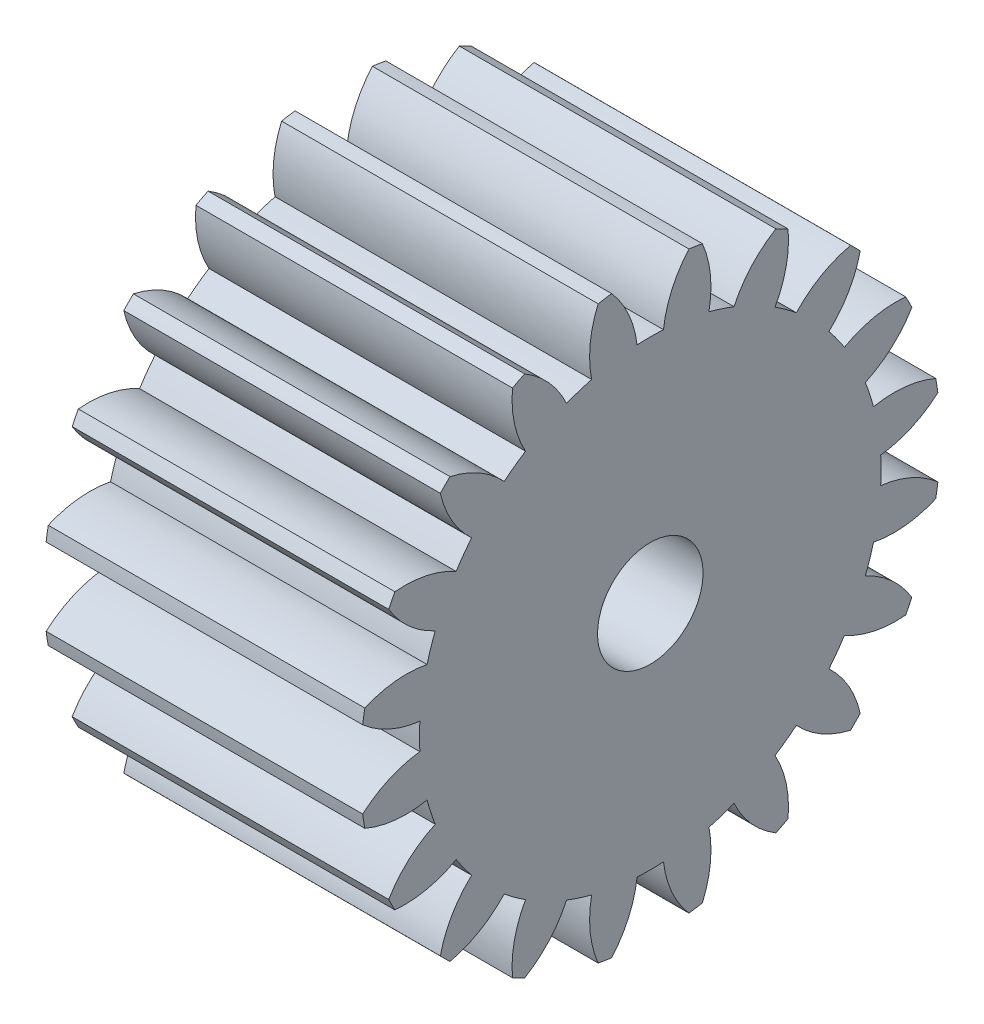
SolidWorks part; units mm, degrees
ref_plane "Plane1" through (0, 0, 0) normal (0, 0, 1) x (1, 0, 0)
ref_plane "Plane2" through (0, 0, 0) normal (0, 1, 0) x (1, 0, 0)
ref_plane "Plane3" through (0, 0, 0) normal (1, 0, 0) x (0, 0, -1)
other "Configuration Table"
sketch "HoldingSke" plane through (0, 0, 0) normal (0, 1, 0) x (1, 0, 0)
  line L0 (0, 0) -> (0.9397, -0.342)
  line L1 (-15, 0) -> (100, 0) construction
  line L2 (0, 0) -> (-2.1039, 2.3779)
  line L3 (0, 0) -> (-11.863, 4.5341)
  line L4 (0, 0) -> (8.1152, 2.9537)
  line L5 (0, 0) -> (-46.8476, -17.4728)
  line L6 (0, 0) -> (-9.9476, -6.7116)
  line L7 (-2.1039, 2.3779) -> (8.6586, 51.2059)
  line L8 (-76.2, 54.61) -> (-75.5, 54.61)
  line L9 (-71.009, 38.7566) -> (-53.1078, 45.2721)
  line L10 (-76.2, 71.12) -> (104.1128, 71.12)
  line L11 (0, 0) -> (-12, 0)
  line L12 (-76.2, 101.6) -> (-76.162, 101.6)
  line L13 (24.9733, 27.94) -> (52.9518, 28.4284)
  line L14 (24.9733, 27.94) -> (24.9743, 27.94)
  line L15 (24.9733, 27.94) -> (100.4006, 29.5858)
  line L16 (-63.627, -1) -> (-12.827, -1)
  circle A0 centre (0, 0) radius 2
  circle A1 centre (0, 0) radius 8.749
  circle A2 centre (0, 0) radius 37.5
  circle A3 centre (0, 0) radius 2
  dimension "MHD" = 17.498
  dimension "Hub_dia" = 75
  dimension "Bore" = 4
  dimension "MBD" = 4
  dimension "Num_teeth" = 20
  dimension "Pitch" = 1
  dimension "Overall_len" = 50
  dimension "Show_teeth" = 20
  dimension "Thickness" = 12
  dimension "OAL" = 50.0001
  dimension "T_dim" = 0.7
  dimension "Ap" = 20
  dimension "H" = 19.05
  dimension "Pitch_radius" = 180.3128
  dimension "Width" = 12
  dimension "Backlash" = 0.038
  dimension "Addendum_fac" = 1
  dimension "Dedendum_fac" = 1.25
  dimension "Clearance_fac" = 0.25
  dimension "Dedendum_add" = 0.001
  dimension "Module" = 1
sketch "BasProSke" plane through (0, 0, 0) normal (0, 1, 0) x (1, 0, 0)
  line L0 (-10, 0) -> (60, 0) construction
  line L1 (0, 0) -> (0, 11)
  line L2 (0, 0) -> (12, 0)
  line L3 (12, 0) -> (12, 11)
  line L4 (12, 11) -> (0, 11)
  dimension "Thickness" = 12
  dimension "Diameter" = 22
revolve "Base-Revolve" add sketch "BasProSke" angle 360 about L0
sketch "TooCutSke" plane through (0, 0, 0) normal (1, 0, 0) x (0, 0, -1)
  line L1 (0, 0) -> (0, 107) construction
  line L2 (0, 0) -> (-0.8511, 9.9637) construction
  line L3 (0, 0) -> (-3.1206, 19.7028) construction
  line L4 (-0.8511, 9.9637) -> (-1.5603, 9.8514) construction
  arc A0 (0.4999, 8.7347) -> (-0.4999, 8.7347) centre (0, 0) ccw
  arc A1 (1.4852, 10.9249) -> (-1.4852, 10.9249) centre (0, 0) ccw
  circle A2 centre (0, 0) radius 10 construction
  circle A3 centre (0, 0) radius 9.3969 construction
  arc A4 (-0.4999, 8.7347) -> (-1.4852, 10.9249) centre (-4.4722, 8.2645) ccw
  arc A5 (1.4852, 10.9249) -> (0.4999, 8.7347) centre (4.4722, 8.2645) ccw
  dimension "Root_dia" = 17.498
  dimension "Overcut_dia" = 22.0508
  dimension "Pitch_dia" = 20
  dimension "Base_dia" = 18.7939
  dimension "Flank_rad" = 4
  dimension "Half_ang" = 9
  dimension "Half_CT" = 0.7181
extrude "ToothCut" cut sketch "TooCutSke" along normal through all
fillet "Breaks" [suppressed] radius 0.02
fillet "RootFillets" [suppressed] radius 0.251
pattern_circular "TeethCuts" count 20 every 18 about axis through (-10, 0, 0) along (1, 0, 0) of "ToothCut", "RootFillets", "Breaks"
sketch "HubNeaOneSke" plane through (0, 0, 0) normal (-1, 0, 0) x (0, 0, 1)
  circle A0 centre (0, 0) radius 8.749
  dimension "Diameter" = 17.498
extrude "HubNearOne" [suppressed] add sketch "HubNeaOneSke" along normal blind 38.0001
sketch "HubNeaBotSke" plane through (0, 0, 0) normal (-1, 0, 0) x (0, 0, 1)
  circle A0 centre (0, 0) radius 8.749
  dimension "Diameter" = 17.498
extrude "HubNearBoth" [suppressed] add sketch "HubNeaBotSke" along normal blind 19
ref_plane "FarPln" through (12, 0, 0) normal (1, 0, 0) x (0, 0, -1)
sketch "HubFarSke" plane through (12, 0, 0) normal (1, 0, 0) x (0, 0, -1)
  circle A0 centre (0, 0) radius 8.749
  dimension "Diameter" = 17.498
extrude "HubFar" [suppressed] add sketch "HubFarSke" along normal blind 19
sketch "BorSke" plane through (0, 0, 0) normal (1, 0, 0) x (0, 0, -1)
  circle A0 centre (0, 0) radius 2
  dimension "Diameter" = 4
extrude "Bore" cut sketch "BorSke" along normal mid plane 100.0001
sketch "KeySke" plane through (0, 0, 0) normal (1, 0, 0) x (0, 0, -1)
  line L0 (-0.8, 0) -> (-0.8, 2.7)
  line L1 (-0.8, 2.7) -> (0.8, 2.7)
  line L2 (0.8, 2.7) -> (0.8, 0)
  line L3 (0, 0) -> (0, 34) construction
  line L4 (-0.8, 0) -> (0.8, 0)
  dimension "Offset" = 2.7
  dimension "Width" = 1.6
extrude "Keyway" [suppressed] cut sketch "KeySke" along normal mid plane 100.0001
pattern_circular "Keyway2" [suppressed] count 2 every 90 about axis through (-10, 0, 0) along (1, 0, 0)
equation "' \"Module@HoldingSke\" = 6.35"
equation "' \"Num_teeth@HoldingSke\" = 12"
equation "' \"Ap@HoldingSke\" =  20"
equation "' \"Ap@HoldingSke\" = 20"
equation "' \"Width@HoldingSke\" = 0.5 * 25.4"
equation "' \"Hub_dia@HoldingSke\"= 1 * 25.4"
equation "' \"Hub_dia@HoldingSke\" = 1 * 25.4"
equation "' \"Overall_len@HoldingSke\" = 1.0 * 25.4"
equation "' \"Bore@HoldingSke\" = 0.75 * 25.4"
equation "' \"T_dim@HoldingSke\" = 0.1 * 25.4"
equation "' \"Width@KeySke\" = 0.25 * 25.4"
equation "' \"Show_teeth@HoldingSke\" = 13"
equation "' \"Backlash@HoldingSke\" = 0.009 * 25.4"
equation "' \"Addendum_fac@HoldingSke\" = 1.0"
equation "' \"Dedendum_fac@HoldingSke\" = 1.25"
equation "' \"Dedendum_add@HoldingSke\" = 0.00005 * 25.4"
equation "' \"Clearance_fac@HoldingSke\" = 0.25"
equation "\"Pitch@HoldingSke\" = 1 / \"Module@HoldingSke\""
equation "\"Overcut_dia@TooCutSke\" = (\"Num_teeth@HoldingSke\" + 2 * \"Addendum_fac@HoldingSke\") / \"Pitch@HoldingSke\" + 0.002 * 25.4"
equation "\"Pitch_dia@TooCutSke\" = \"Num_teeth@HoldingSke\" / \"Pitch@HoldingSke\""
equation "\"Base_dia@TooCutSke\" = \"Num_teeth@HoldingSke\" / \"Pitch@HoldingSke\" * cos((\"Ap@HoldingSke\"  * 3.14159265 / 180))"
equation "\"Root_dia@TooCutSke\" = (\"Num_teeth@HoldingSke\" + 2) / \"Pitch@HoldingSke\" - 2 * (\"Addendum_fac@HoldingSke\" + \"Dedendum_fac@HoldingSke\") / \"Pitch@HoldingSke\" - \"Dedendum_add@HoldingSke\" * 2"
equation "\"Half_ang@TooCutSke\" = 180 / \"Num_teeth@HoldingSke\""
equation "\"Half_CT@TooCutSke\" = \"Num_teeth@HoldingSke\" / \"Pitch@HoldingSke\" * sin((3.14159265 / 2 / \"Num_teeth@HoldingSke\")) / 2 - 7 * \"Backlash@HoldingSke\" / 4"
equation "\"Flank_rad@TooCutSke\" = \"Num_teeth@HoldingSke\" / \"Pitch@HoldingSke\" / 5"
equation "\"Radius@RootFillets\" = \"Clearance_fac@HoldingSke\" / \"Pitch@HoldingSke\" + \"Dedendum_add@HoldingSke\""
equation "\"Break_rad@Breaks\" = 0.02 / \"Pitch@HoldingSke\""
equation "\"Thickness@HoldingSke\" = \"Width@HoldingSke\""
equation "\"OAL@HoldingSke\" = \"Thickness@HoldingSke\""
equation "\"MHD@HoldingSke\" = (\"Num_teeth@HoldingSke\" + 2) / \"Pitch@HoldingSke\" - 2 * (\"Addendum_fac@HoldingSke\" + \"Dedendum_fac@HoldingSke\")  / \"Pitch@HoldingSke\" - \"Dedendum_add@HoldingSke\" * 2"
equation "\"MBD@HoldingSke\" = (\"Num_teeth@HoldingSke\" + 2) / \"Pitch@HoldingSke\" - 2 * (\"Addendum_fac@HoldingSke\" + \"Dedendum_fac@HoldingSke\")  / \"Pitch@HoldingSke\" - \"Dedendum_add@HoldingSke\" * 2 - 0.002 * 25.4"
equation "\"MHD@HoldingSke\" = ((sgn( \"MHD@HoldingSke\" - \"Hub_dia@HoldingSke\" )-1)*( \"MHD@HoldingSke\" - \"Hub_dia@HoldingSke\" ))/-2+ \"Hub_dia@HoldingSke\""
equation "\"MBD@HoldingSke\" = ((sgn( \"MBD@HoldingSke\" - \"Bore@HoldingSke\" )-1)*( \"MBD@HoldingSke\" - \"Bore@HoldingSke\" ))/-2+ \"Bore@HoldingSke\""
equation "\"OAL@HoldingSke\" = ((sgn( \"OAL@HoldingSke\" - \"Overall_len@HoldingSke\" )+1)*( \"OAL@HoldingSke\" - \"Overall_len@HoldingSke\" ))/2 + \"Overall_len@HoldingSke\" + 0.000002 * 25.4"
equation "\"Num_teeth@TeethCuts\" = int( \"Show_teeth@HoldingSke\" ) + 1"
equation "\"Num_teeth@TeethCuts\" = ((sgn( \"Num_teeth@TeethCuts\" - \"Num_teeth@HoldingSke\" )-1)*( \"Num_teeth@TeethCuts\" - \"Num_teeth@HoldingSke\" ))/-2+ \"Num_teeth@HoldingSke\""
equation "\"Num_teeth@TeethCuts\" = ((sgn( \"Num_teeth@TeethCuts\" - 2.0)+1)*( \"Num_teeth@TeethCuts\" - 2.0))/2 +2.0"
equation "\"Angle@TeethCuts\" = 360.0 / \"Num_teeth@HoldingSke\""
equation "\"Diameter@BasProSke\" = (\"Num_teeth@HoldingSke\" + 2 * \"Addendum_fac@HoldingSke\") / \"Pitch@HoldingSke\""
equation "\"Thickness@BasProSke\"  = \"Thickness@HoldingSke\""
equation "' \"Fillet_rad@BasProSke\" =  \"Thickness@HoldingSke\" * 0.05"
equation "' \"Fillet_rad@BasProSke\" = \"Thickness@HoldingSke\" * 0.05"
equation "\"MHD@HoldingSke\" = ((sgn( \"MHD@HoldingSke\" - \"Root_dia@TooCutSke\" )-1)*( \"MHD@HoldingSke\" - \"Root_dia@TooCutSke\" ))/-2+ \"Root_dia@TooCutSke\""
equation "\"Diameter@HubNeaOneSke\" = \"MHD@HoldingSke\""
equation "\"Length@HubNearOne\" = \"OAL@HoldingSke\" - \"Thickness@BasProSke\""
equation "\"Diameter@HubNeaBotSke\" = \"MHD@HoldingSke\""
equation "\"Length@HubNearBoth\" = ( \"OAL@HoldingSke\" - \"Thickness@BasProSke\" ) / 2.0"
equation "\"Thickness@FarPln\" = \"Thickness@BasProSke\""
equation "\"Diameter@HubFarSke\" = \"MHD@HoldingSke\""
equation "\"Length@HubFar\" = ( \"OAL@HoldingSke\" - \"Thickness@BasProSke\" ) / 2.0"
equation "\"Diameter@BorSke\" = \"MBD@HoldingSke\""
equation "\"D1@Bore\" = \"OAL@HoldingSke\" * 2.0"
equation "\"D1@Keyway\" = \"OAL@HoldingSke\" * 2.0"
equation "\"Offset@KeySke\" = \"T_dim@HoldingSke\" + \"MBD@HoldingSke\" / 2.0"
